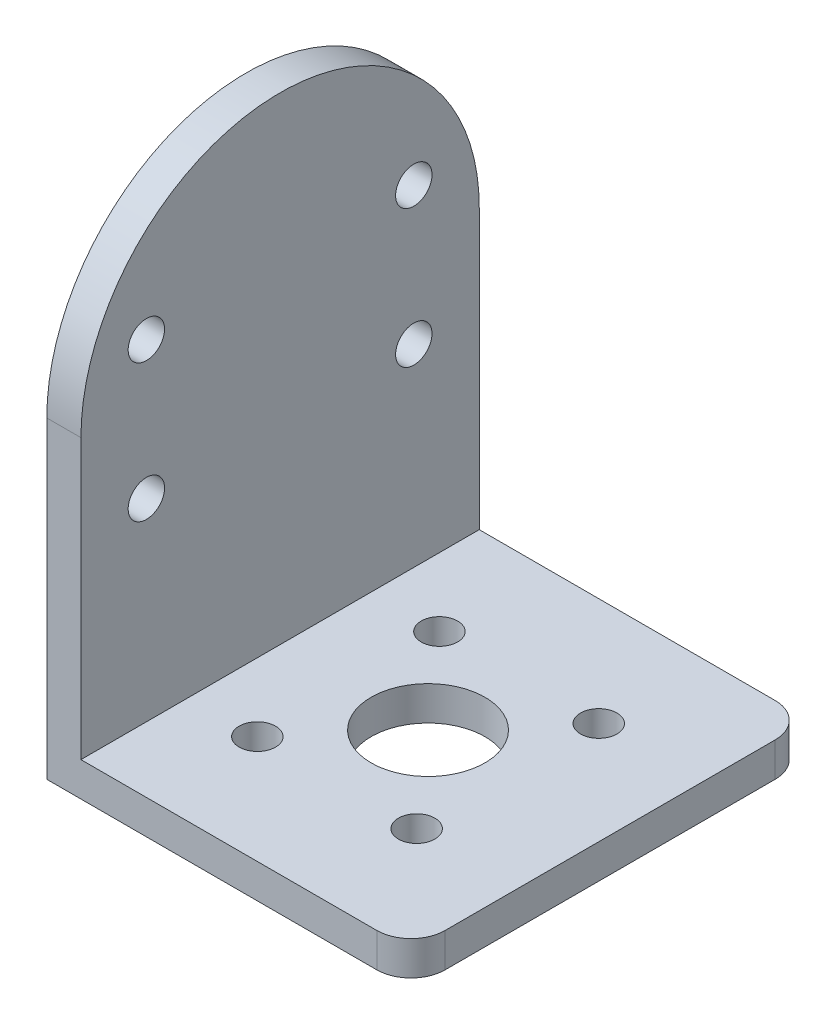
SolidWorks part; units mm, degrees
ref_plane "前视基准面" through (0, 0, 0) normal (0, 0, 1) x (1, 0, 0)
ref_plane "上视基准面" through (0, 0, 0) normal (0, 1, 0) x (1, 0, 0)
ref_plane "右视基准面" through (0, 0, 0) normal (1, 0, 0) x (0, 0, -1)
sketch "草图1" plane through (0, 0, 0) normal (0, 0, 1) x (1, 0, 0)
  line L0 (0, 0) -> (0, 45)
  line L1 (0, 45) -> (3, 45)
  line L2 (3, 45) -> (3, 3)
  line L3 (3, 3) -> (32, 3)
  line L4 (32, 3) -> (32, 0)
  line L5 (32, 0) -> (0, 0)
  dimension "D1" = 3
  dimension "D2" = 45
  dimension "D3" = 32
extrude "凸台-拉伸1" add sketch "草图1" along normal mid plane 35
sketch "草图2" plane through (3, 0, 0) normal (1, 0, 0) x (0, 0, -1)
  line L1 (17.5, 45) -> (17.5, 27.5)
  line L4 (0, 20) -> (0, 0) construction
  line L7 (17.5, 3) -> (17.5, 45)
  line L8 (17.5, 45) -> (-17.5, 45)
  line L9 (-17.5, 45) -> (-17.5, 3)
  line L10 (-17.5, 3) -> (17.5, 3)
  line L12 (17.5, 45) -> (-17.5, 45)
  line L13 (-17.5, 45) -> (-17.5, 27.5)
  line L15 (-17.5, 27.5) -> (-17.5, 45)
  circle A3 centre (-11.75, 20) radius 1.6
  circle A4 centre (11.75, 20) radius 1.6
  arc A5 (17.5, 27.5) -> (-17.5, 27.5) centre (0, 27.5) ccw
  circle A6 centre (-11.75, 32.09) radius 1.6
  circle A7 centre (11.75, 32.09) radius 1.6
  point P18 (0, 0)
  point P19 (0, 0)
  point P20 (0, 0)
  dimension "D5" = 3.2
  dimension "D6" = 11.75
  dimension "D2" = 20
  dimension "D7" = 12.09
  dimension "D1" = 0
extrude "切除-拉伸2" cut sketch "草图2" against normal blind 26
sketch "草图3" plane through (0, 3, 0) normal (0, 1, 0) x (1, 0, 0)
  line L0 (32, -17.5) -> (32, 17.5) construction
  line L1 (16, 0) -> (32, 0) construction
  line L3 (23, -8) -> (9, -8) construction
  line L4 (23, -8) -> (23, 8) construction
  line L5 (23, 8) -> (9, 8) construction
  line L6 (9, -8) -> (9, 8) construction
  line L7 (23, -8) -> (9, 8) construction
  line L8 (23, 8) -> (9, -8) construction
  circle A0 centre (16, 0) radius 5
  circle A1 centre (9, 8) radius 1.6
  circle A2 centre (23, 8) radius 1.6
  circle A3 centre (23, -8) radius 1.6
  circle A4 centre (9, -8) radius 1.6
  dimension "D2" = 10
  dimension "D5" = 3.2
  dimension "D1" = 16
  dimension "D3" = 16
  dimension "D4" = 14
extrude "切除-拉伸3" cut sketch "草图3" against normal through all
fillet "圆角2" radius 3 2 edges at (32, 1.5, 17.5) (32, 1.5, -17.5)
